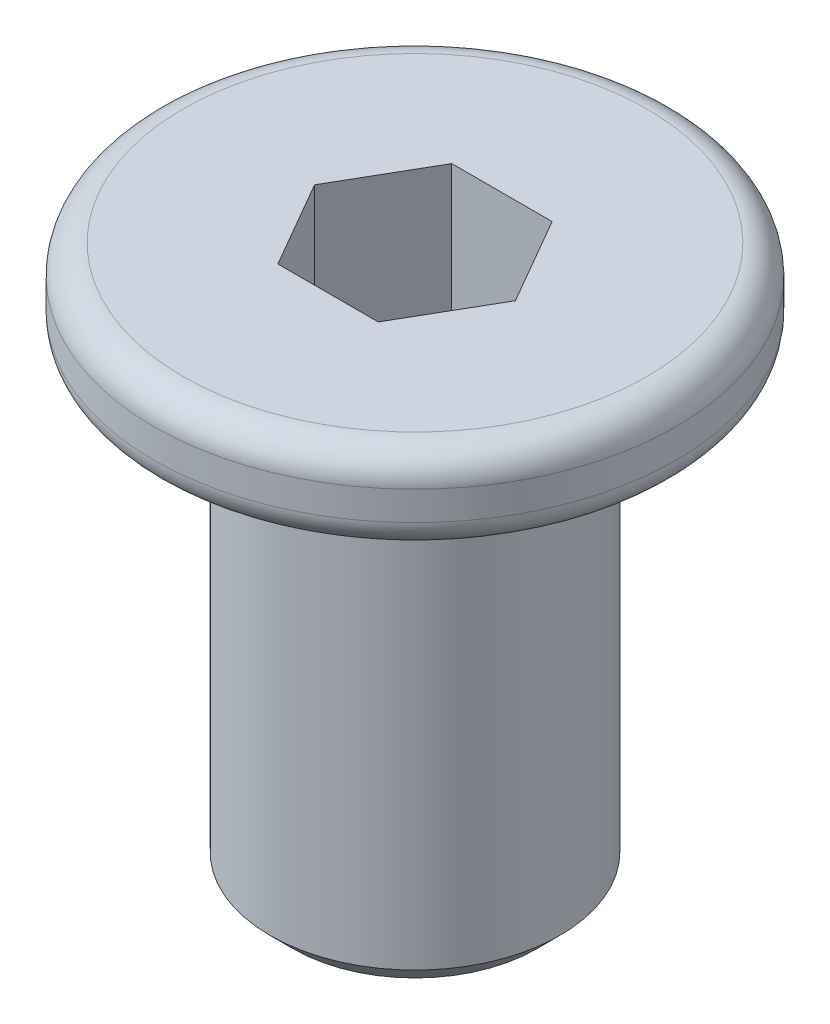
SolidWorks part; units mm, degrees
ref_plane "Front Plane" through (0, 0, 0) normal (0, 0, 1) x (1, 0, 0)
ref_plane "Top Plane" through (0, 0, 0) normal (0, 1, 0) x (1, 0, 0)
ref_plane "Right Plane" through (0, 0, 0) normal (1, 0, 0) x (0, 0, -1)
sketch "Sketch1" plane through (0, 0, 0) normal (0, 0, 1) x (1, 0, 0)
  line L1 (-4.5, -0.5) -> (-4.5, -1)
  line L2 (-4, -1.5) -> (-2.5, -1.5)
  line L3 (-2.5, -1.5) -> (-2.5, -9.1)
  line L5 (0, 2.75) -> (0, -11.9483) construction
  line L7 (-4, 0) -> (-1.5, 0)
  line L8 (-1.5, 0) -> (-1.5, -3)
  line L9 (-1.5, -3) -> (0, -4)
  line L10 (-2.1, -9.5) -> (0, -9.5)
  line L11 (-2.5, -9.1) -> (-2.1, -9.5)
  line L12 (0, -4) -> (0, -9.5)
  arc A1 (-4.5, -1) -> (-4, -1.5) centre (-4, -1) ccw
  arc A2 (-4, 0) -> (-4.5, -0.5) centre (-4, -0.5) ccw
  point P15 (-2.5, -9.5)
  dimension "D5" = 0.5
  dimension "D6" = 1.5
  dimension "D1" = 3
  dimension "D2" = 9
  dimension "D3" = 8
  dimension "D4" = 5
  dimension "D7" = 3
  dimension "D8" = 1
revolve "Revolve1" add sketch "Sketch1" angle 360 about L5
sketch "Sketch3" plane through (0, 0, 0) normal (0, 1, 0) x (1, 0, 0)
  line L1 (-0.866, -1.5) -> (0.866, -1.5)
  line L2 (0.866, -1.5) -> (1.7321, 0)
  line L3 (1.7321, 0) -> (0.866, 1.5)
  line L4 (0.866, 1.5) -> (-0.866, 1.5)
  line L5 (-0.866, 1.5) -> (-1.7321, 0)
  line L6 (-1.7321, 0) -> (-0.866, -1.5)
  circle A0 centre (0, 0) radius 1.5 construction
  circle A1 centre (0, 0) radius 1.5 construction
extrude "Cut-Extrude2" cut sketch "Sketch3" against normal blind 3
